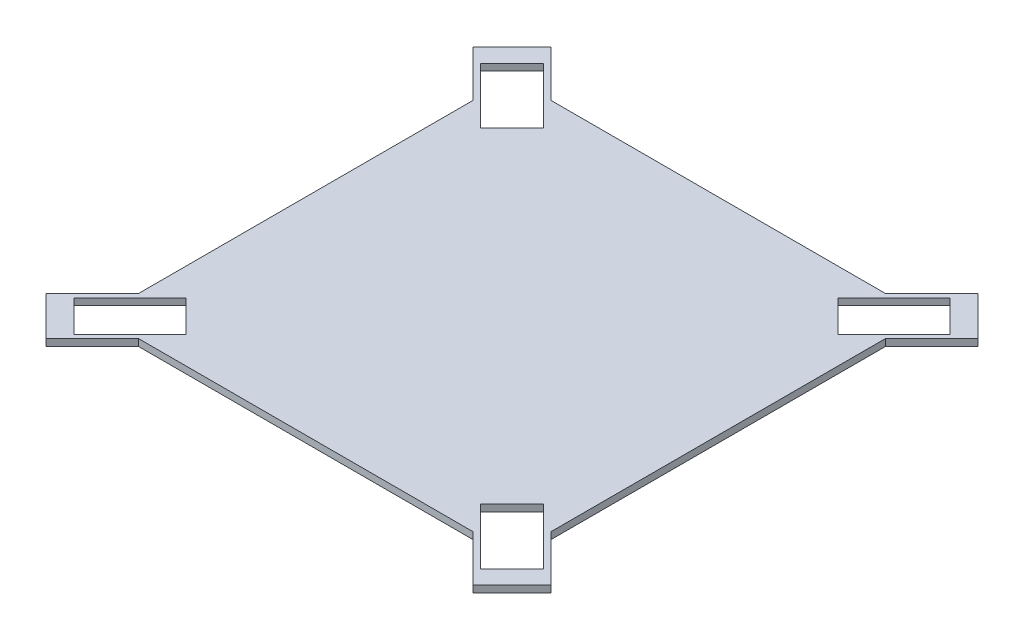
SolidWorks part; units mm, degrees
ref_plane "Front Plane" through (0, 0, 0) normal (0, 0, 1) x (1, 0, 0)
ref_plane "Top Plane" through (0, 0, 0) normal (0, 1, 0) x (1, 0, 0)
ref_plane "Right Plane" through (0, 0, 0) normal (1, 0, 0) x (0, 0, -1)
sketch "Sketch1" plane through (0, 0, 0) normal (0, 1, 0) x (1, 0, 0)
  line L0 (-823.8606, -823.8606) -> (40265.2987, 40265.2987) construction
  line L1 (48.6562, -59.9699) -> (-48.6562, -59.9699)
  line L2 (59.9699, -48.6562) -> (59.9699, 48.6562)
  line L3 (48.6562, 59.9699) -> (-48.6562, 59.9699)
  line L5 (60.7501, -60.7501) -> (-60.7501, 60.7501) construction
  line L6 (59.2404, 59.2404) -> (-59.9832, -59.9832) construction
  line L7 (62.0912, 73.4049) -> (73.4049, 62.0912)
  line L8 (62.0912, 73.4049) -> (48.6562, 59.9699)
  line L9 (73.4049, 62.0912) -> (59.9699, 48.6562)
  line L11 (59.0506, 68.243) -> (68.243, 59.0506)
  line L12 (59.0506, 68.243) -> (42.7872, 51.9796)
  line L13 (68.243, 59.0506) -> (51.9796, 42.7872)
  line L14 (42.7872, 51.9796) -> (51.9796, 42.7872)
  line L15 (-1000, 0) -> (49000, 0) construction
  line L16 (0, -1000) -> (0, 49000) construction
  line L17 (73.4049, -62.0912) -> (59.9699, -48.6562)
  line L18 (62.0912, -73.4049) -> (73.4049, -62.0912)
  line L19 (62.0912, -73.4049) -> (48.6562, -59.9699)
  line L20 (68.243, -59.0506) -> (51.9796, -42.7872)
  line L21 (42.7872, -51.9796) -> (51.9796, -42.7872)
  line L22 (59.0506, -68.243) -> (42.7872, -51.9796)
  line L23 (59.0506, -68.243) -> (68.243, -59.0506)
  line L24 (-62.0912, -73.4049) -> (-48.6562, -59.9699)
  line L25 (-62.0912, -73.4049) -> (-73.4049, -62.0912)
  line L26 (-73.4049, -62.0912) -> (-59.9699, -48.6562)
  line L27 (-59.0506, -68.243) -> (-68.243, -59.0506)
  line L28 (-59.0506, -68.243) -> (-42.7872, -51.9796)
  line L29 (-42.7872, -51.9796) -> (-51.9796, -42.7872)
  line L30 (-68.243, -59.0506) -> (-51.9796, -42.7872)
  line L31 (-73.4049, 62.0912) -> (-59.9699, 48.6562)
  line L32 (-62.0912, 73.4049) -> (-48.6562, 59.9699)
  line L33 (-62.0912, 73.4049) -> (-73.4049, 62.0912)
  line L34 (-68.243, 59.0506) -> (-51.9796, 42.7872)
  line L35 (-42.7872, 51.9796) -> (-51.9796, 42.7872)
  line L36 (-59.0506, 68.243) -> (-42.7872, 51.9796)
  line L37 (-59.0506, 68.243) -> (-68.243, 59.0506)
  line L39 (-59.9699, -48.6562) -> (-59.9699, 48.6562)
  point P0 (0, 0)
  point P7 (67.7481, 67.7481)
  point P11 (63.6468, 63.6468)
  point P46 (-47.3834, 47.3834)
  point P47 (47.3834, 47.3834)
  dimension "D1" = 120
  dimension "D2" = 120
  dimension "D3" = 19
  dimension "D4" = 16
  dimension "D5" = 19
  dimension "D6" = 23
  dimension "D7" = 13
  dimension "D8" = 5.8
  dimension "D9" = 90
  dimension "D10" = 97.3123
extrude "Boss-Extrude1" add sketch "Sketch1" along normal blind 2
